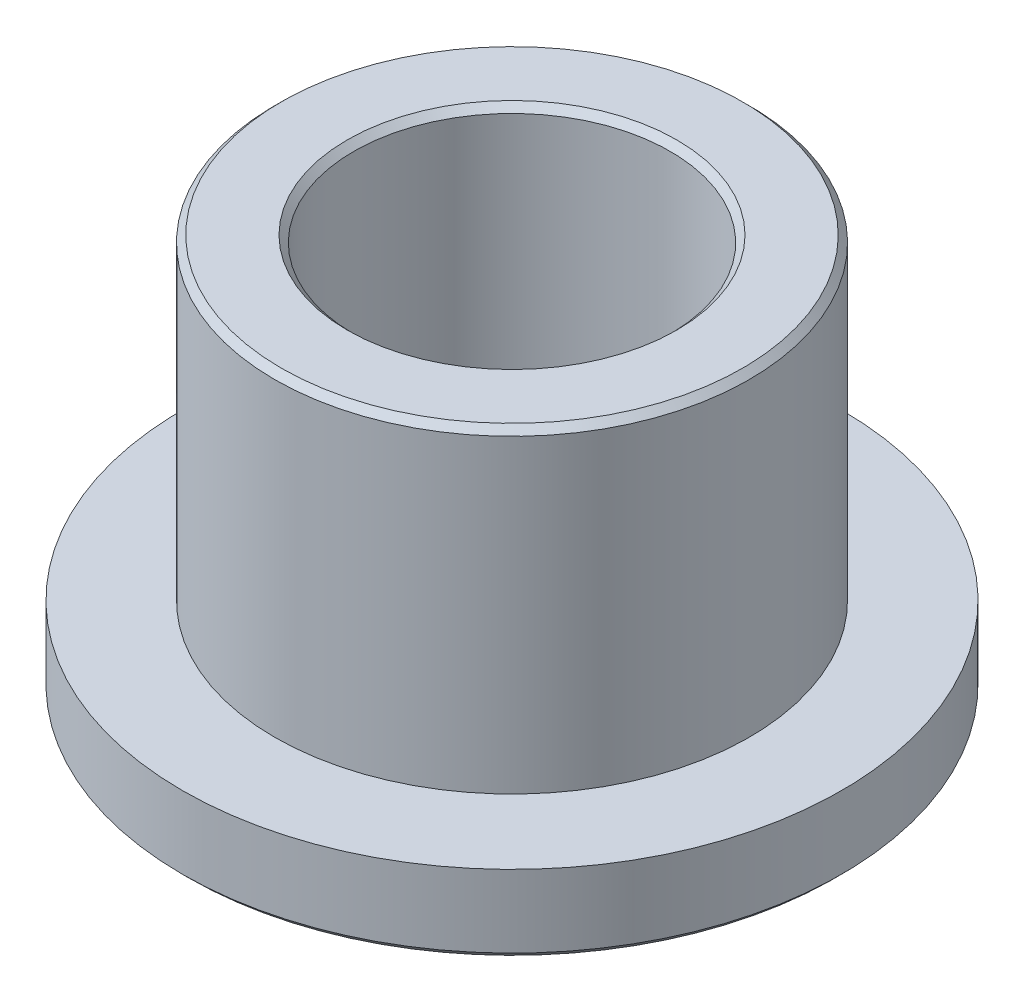
SolidWorks part; units mm, degrees
material "黄铜"
ref_plane "前视基准面" through (0, 0, 0) normal (0, 0, 1) x (1, 0, 0)
ref_plane "上视基准面" through (0, 0, 0) normal (0, 1, 0) x (1, 0, 0)
ref_plane "右视基准面" through (0, 0, 0) normal (1, 0, 0) x (0, 0, -1)
sketch "草图1" plane through (0, 0, 0) normal (0, 1, 0) x (1, 0, 0)
  circle A0 centre (0, 0) radius 12.5
  circle A1 centre (0, 0) radius 6
extrude "凸台-拉伸1" add sketch "草图1" along normal blind 3
sketch "草图2" plane through (0, 3, 0) normal (0, 1, 0) x (1, 0, 0)
  circle A0 centre (0, 0) radius 6 construction
  circle A1 centre (0, 0) radius 6
  circle A2 centre (0, 0) radius 9
extrude "凸台-拉伸2" add sketch "草图2" along normal blind 12
chamfer "倒角1" distance 0.25 angle 45 4 edges at (0, 0, 6) (0, 0, 12.5) (0, 15, 6) (0, 15, 9)
